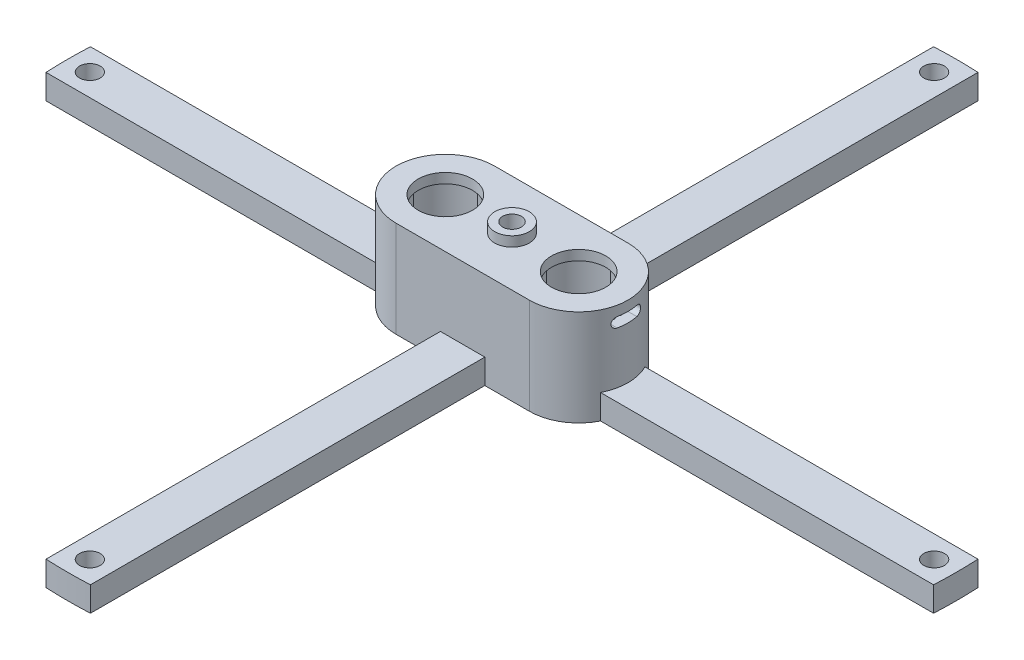
SolidWorks part; units mm, degrees
ref_plane "Front Plane" through (0, 0, 0) normal (0, 0, 1) x (1, 0, 0)
ref_plane "Top Plane" through (0, 0, 0) normal (0, 1, 0) x (1, 0, 0)
ref_plane "Right Plane" through (0, 0, 0) normal (1, 0, 0) x (0, 0, -1)
sketch "Sketch1" plane through (0, 0, 0) normal (0, 1, 0) x (1, 0, 0)
  line L0 (-44.9437, 2.25) -> (-11.2151, 2.25)
  line L1 (-44.9437, -2.25) -> (-11.2151, -2.25)
  line L2 (2.25, 44.9437) -> (2.25, 5)
  line L3 (-2.25, 44.9437) -> (-2.25, 5)
  line L4 (44.9437, -2.25) -> (11.2151, -2.25)
  line L5 (44.9437, 2.25) -> (11.2151, 2.25)
  line L6 (-2.25, -44.9437) -> (-2.25, -5)
  line L7 (2.25, -44.9437) -> (2.25, -5)
  line L16 (-6.1349, 0) -> (6.1349, 0) construction
  line L17 (-2.25, 5) -> (-6.75, 5)
  line L18 (2.25, 5) -> (6.75, 5)
  line L19 (-2.25, -5) -> (-6.75, -5)
  line L20 (2.25, -5) -> (6.75, -5)
  circle A0 centre (0, 0) radius 45 construction
  circle A3 centre (-42.75, 0) radius 2.25 construction
  arc A4 (-44.9437, 2.25) -> (-44.9437, -2.25) centre (0, 0) ccw
  arc A7 (2.25, 44.9437) -> (-2.25, 44.9437) centre (0, 0) ccw
  circle A9 centre (0, 42.75) radius 2.25 construction
  arc A11 (44.9437, -2.25) -> (44.9437, 2.25) centre (0, 0) ccw
  circle A13 centre (42.75, 0) radius 2.25 construction
  arc A15 (-2.25, -44.9437) -> (2.25, -44.9437) centre (0, 0) ccw
  circle A17 centre (0, -42.75) radius 2.25 construction
  circle A18 centre (0, 0) radius 0.95
  circle A23 centre (-6.75, 0) radius 5 construction
  circle A28 centre (6.75, 0) radius 5 construction
  arc A30 (6.75, 5) -> (6.75, -5) centre (6.75, 0) ccw
  arc A31 (-6.75, -5) -> (-6.75, 5) centre (-6.75, 0) ccw
  arc A32 (11.2151, 2.25) -> (11.2151, -2.25) centre (6.75, 0) cw
  arc A33 (-11.2151, 2.25) -> (-11.2151, -2.25) centre (-6.75, 0) ccw
  circle A34 centre (-42.75, 0) radius 1.05
  circle A35 centre (0, 42.75) radius 1.05
  circle A36 centre (42.75, 0) radius 1.05
  circle A37 centre (0, -42.75) radius 1.05
  point P8 (0, 0)
  dimension "D1" = 90
  dimension "D2" = 6.75
  dimension "D3" = 2.1
  dimension "D4" = 4.5
  dimension "D5" = 10
  dimension "D8" = 42.75
  dimension "D9" = 4
  dimension "D7" = 10
  dimension "D6" = 6.75
extrude "Boss-Extrude1" add sketch "Sketch1" along normal blind 2.5 contours L1 A33 L0 A4 | L2 L18 A30 L20 L7 A15 L6 L19 A31 L17 L3 A7 | L4 A32 L5 A11 | A34 | A37 | A36 | A35 | A18
sketch "Sketch2" plane through (0, 0, 0) normal (0, 1, 0) x (1, 0, 0)
  line L0 (0, 0) -> (-6.75, 0) construction
  line L1 (-13.4792, 0.75) -> (-11.6934, 0.75)
  line L2 (-13.4792, -0.75) -> (-11.6934, -0.75)
  line L3 (-12.5007, -0.75) -> (-12.5007, 0.75) construction
  line L4 (-17.25, 0) -> (16.25, 0) construction
  line L5 (-7, 3.9922) -> (-7, 3.4922)
  line L6 (-6.5, 3.9922) -> (-6.5, 3.4922)
  line L7 (-6.75, 0) -> (-6.75, 4) construction
  line L9 (-7, 3.4922) -> (-6.5, 3.4922)
  line L10 (-3.2578, 0.25) -> (-3.2578, -0.25)
  line L11 (-2.7578, 0.25) -> (-3.2578, 0.25)
  line L12 (-2.7578, -0.25) -> (-3.2578, -0.25)
  line L13 (-6.5, -3.4922) -> (-7, -3.4922)
  line L14 (-6.5, -3.9922) -> (-6.5, -3.4922)
  line L15 (-7, -3.9922) -> (-7, -3.4922)
  line L16 (-10.2422, -0.25) -> (-10.2422, 0.25)
  line L17 (-10.7422, -0.25) -> (-10.2422, -0.25)
  line L18 (-10.7422, 0.25) -> (-10.2422, 0.25)
  line L30 (6.5, 3.9922) -> (6.5, 3.4922)
  line L31 (6.5, 3.4922) -> (7, 3.4922)
  line L32 (7, 3.9922) -> (7, 3.4922)
  line L33 (10.7422, 0.25) -> (10.2422, 0.25)
  line L34 (10.2422, 0.25) -> (10.2422, -0.25)
  line L35 (10.7422, -0.25) -> (10.2422, -0.25)
  line L36 (7, -3.9922) -> (7, -3.4922)
  line L37 (7, -3.4922) -> (6.5, -3.4922)
  line L38 (6.5, -3.9922) -> (6.5, -3.4922)
  line L39 (2.7578, -0.25) -> (3.2578, -0.25)
  line L40 (3.2578, -0.25) -> (3.2578, 0.25)
  line L41 (2.7578, 0.25) -> (3.2578, 0.25)
  line L42 (-6.75, 5) -> (6.75, 5)
  line L43 (-6.75, -5) -> (6.75, -5)
  line L44 (-3.75, 4) -> (3.75, 4)
  line L45 (-6.75, 4) -> (6.75, 4) construction
  line L46 (-3.75, -4) -> (3.75, -4)
  line L47 (-6.75, -4) -> (6.75, -4) construction
  arc A2 (-1.8194, -0.8304) -> (1.8194, -0.8304) centre (0, 0) ccw
  circle A3 centre (0, 0) radius 0.95
  arc A4 (-6.75, 5) -> (-6.75, -5) centre (-6.75, 0) ccw
  arc A5 (-10.7422, -0.25) -> (-7, -3.9922) centre (-6.75, 0) ccw
  arc A6 (-6.5, -3.9922) -> (-2.7578, -0.25) centre (-6.75, 0) ccw
  arc A7 (-2.7578, 0.25) -> (-6.5, 3.9922) centre (-6.75, 0) ccw
  arc A8 (-7, 3.9922) -> (-10.7422, 0.25) centre (-6.75, 0) ccw
  arc A15 (-1.8194, 0.8304) -> (-3.75, 4) centre (-6.75, 0) ccw
  arc A16 (-1.8194, -0.8304) -> (1.8194, -0.8304) centre (0, 0) ccw
  arc A17 (3.75, 4) -> (1.8194, 0.8304) centre (6.75, 0) ccw
  arc A18 (7, -3.9922) -> (10.7422, -0.25) centre (6.75, 0) ccw
  arc A19 (10.7422, 0.25) -> (7, 3.9922) centre (6.75, 0) ccw
  arc A20 (2.7578, -0.25) -> (6.5, -3.9922) centre (6.75, 0) ccw
  arc A21 (6.5, 3.9922) -> (2.7578, 0.25) centre (6.75, 0) ccw
  arc A22 (-6.75, 5) -> (-6.75, -5) centre (-6.75, 0) ccw
  arc A23 (-3.75, -4) -> (-1.8194, -0.8304) centre (-6.75, 0) ccw
  arc A24 (-3.75, -4) -> (-1.8194, -0.8304) centre (-6.75, 0) ccw
  arc A25 (6.75, -5) -> (6.75, 5) centre (6.75, 0) ccw
  arc A26 (-1.8194, 0.8304) -> (-3.75, 4) centre (-6.75, 0) ccw
  arc A27 (1.8194, -0.8304) -> (3.75, -4) centre (6.75, 0) ccw
  arc A28 (1.8194, 0.8304) -> (-1.8194, 0.8304) centre (0, 0) ccw
  arc A29 (1.8194, 0.8304) -> (-1.8194, 0.8304) centre (0, 0) ccw
  point P15 (-12.5007, 0)
  point P22 (-6.75, 2)
  point P24 (-6.75, 0)
  dimension "D2" = 2
  dimension "D3" = 1
  dimension "D4" = 1.9
  dimension "D5" = 10
  dimension "D6" = 1
  dimension "D7" = 6.75
  dimension "D8" = 1.5
  dimension "D9" = 0.5
  dimension "D10" = 0.5
  dimension "D12" = 1
  dimension "D11" = 4
extrude "Boss-Extrude2" add sketch "Sketch2" along normal blind 9.75
sketch "Sketch3" plane through (0, 9.75, 0) normal (0, 1, 0) x (1, 0, 0)
  line L0 (-6.75, -5) -> (6.75, -5) construction
  line L1 (-6.75, 5) -> (6.75, 5)
  line L2 (-6.75, -5) -> (6.75, -5)
  circle A1 centre (0, 0) radius 0.95
  circle A2 centre (-6.75, 0) radius 4 construction
  arc A3 (-6.75, 5) -> (-6.75, -5) centre (-6.75, 0) ccw
  arc A4 (6.75, 5) -> (6.75, -5) centre (6.75, 0) cw
  circle A5 centre (-6.75, 0) radius 2.75
  circle A6 centre (6.75, 0) radius 4 construction
  arc A7 (6.75, -5) -> (6.75, 5) centre (6.75, 0) ccw construction
  circle A9 centre (6.75, 0) radius 2.75
  dimension "D1" = 1.9
  dimension "D2" = 5.5
  dimension "D3" = 5.5
extrude "Boss-Extrude3" add sketch "Sketch3" against normal blind 1
sketch "Sketch4" plane through (0, 9.75, 0) normal (0, 1, 0) x (1, 0, 0)
  circle A0 centre (0, 0) radius 1.75
  circle A1 centre (0, 0) radius 0.95
  dimension "D1" = 3.5
  dimension "D2" = 1.9
extrude "Boss-Extrude4" add sketch "Sketch4" along normal blind 1
ref_plane "Plane1" through (11.75, 0, 0) normal (1, 0, 0) x (0, 0, -1)
sketch "Sketch7" plane through (11.75, 0, 0) normal (1, 0, 0) x (0, 0, -1)
  line L0 (-1, 8.25) -> (1, 8.25) construction
  line L1 (-1, 8.75) -> (1, 8.75)
  line L2 (-1, 7.75) -> (1, 7.75)
  line L3 (0, 0) -> (0, 8.75) construction
  line L4 (-2.25, 0) -> (2.25, 0) construction
  arc A0 (-1, 8.75) -> (-1, 7.75) centre (-1, 8.25) ccw
  arc A1 (1, 7.75) -> (1, 8.75) centre (1, 8.25) ccw
  point P2 (0, 8.25)
  dimension "D1" = 1
  dimension "D2" = 2
extrude "Cut-Extrude3" cut sketch "Sketch7" against normal blind 2
